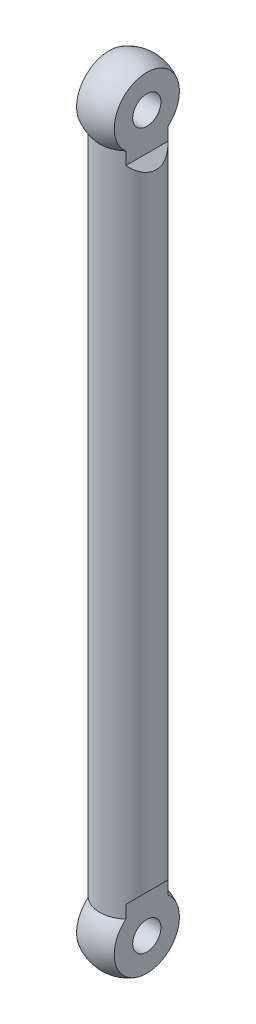
SolidWorks part; units mm, degrees
ref_plane "前视基准面" through (0, 0, 0) normal (0, 0, 1) x (1, 0, 0)
ref_plane "上视基准面" through (0, 0, 0) normal (0, 1, 0) x (1, 0, 0)
ref_plane "右视基准面" through (0, 0, 0) normal (1, 0, 0) x (0, 0, -1)
other "Configuration Table"
sketch "草图1" plane through (0, 0, 0) normal (1, 0, 0) x (0, 0, -1)
  line L1 (0, -21.6284) -> (0, 96.326) construction
  line L2 (0, 80) -> (0, -4)
  line L3 (3, 73.3542) -> (3, 2.6458)
  arc A4 (0, -4) -> (3, 2.6458) centre (0, 0) ccw
  arc A5 (3, 73.3542) -> (0, 80) centre (0, 76) ccw
  dimension "D1" = 76
  dimension "D2" = 3
revolve "旋转7" add sketch "草图1" angle 360 about L1
sketch "草图2" plane through (0, 0, 0) normal (0, 0, 1) x (1, 0, 0)
  line L0 (2, 85.1452) -> (2, 72)
  line L1 (2, 72) -> (3, 71)
  line L2 (3, 2.6458) -> (3, 73.3542) construction
  line L3 (3, 71) -> (8.1115, 71)
  line L4 (8.1115, 71) -> (8.1115, 85.1452)
  line L5 (8.1115, 85.1452) -> (2, 85.1452)
  line L6 (0, -21.6284) -> (0, 96.326) construction
  line L7 (0, 73.3542) -> (0, 2.6458) construction
  line L8 (0, 38) -> (35.9032, 38) construction
  line L9 (8.1115, -9.1452) -> (2, -9.1452)
  line L10 (8.1115, 5) -> (8.1115, -9.1452)
  line L11 (3, 5) -> (8.1115, 5)
  line L12 (2, 4) -> (3, 5)
  line L13 (2, -9.1452) -> (2, 4)
  point P11 (0, 38)
  dimension "D1" = 2
  dimension "D2" = 45
  dimension "D3" = 34
  dimension "D4" = 6.1115
  dimension "D5" = 14.1452
extrude "切除-拉伸1" cut sketch "草图2" against normal through all both and the other way through all
mirror "镜向1" about plane through (0, 0, 0) normal (1, 0, 0) of "切除-拉伸1"
sketch "草图3" plane through (2, 0, 0) normal (1, 0, 0) x (0, 0, -1)
  circle A0 centre (0, 76) radius 1.5
  circle A1 centre (0, 0) radius 1.5
extrude "切除-拉伸2" cut sketch "草图3" against normal through all both and the other way through all contours A0
sketch "草图4" plane through (2, 0, 0) normal (1, 0, 0) x (0, 0, -1)
  circle A0 centre (0, 0) radius 1.5
extrude "切除-拉伸3" cut sketch "草图4" against normal through all both and the other way through all
